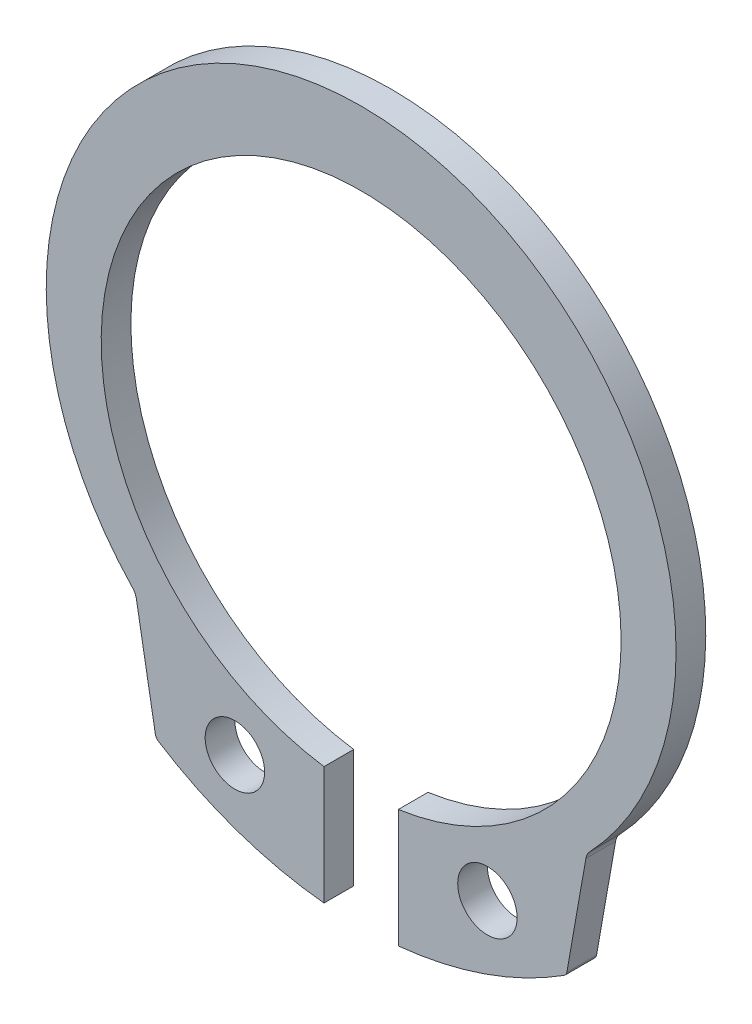
SolidWorks part; units mm, degrees
ref_plane "Front" through (0, 0, 0) normal (0, 0, 1) x (1, 0, 0)
ref_plane "Top" through (0, 0, 0) normal (0, 1, 0) x (1, 0, 0)
ref_plane "Right" through (0, 0, 0) normal (1, 0, 0) x (0, 0, -1)
sketch "Sketch1" plane through (0, 0, 0) normal (0, 0, 1) x (1, 0, 0)
  line L0 (0, 4.2365) -> (0, -4.9012) construction
  line L1 (-1.25, -9.2803) -> (-1.25, -13.2583)
  line L2 (1.25, -9.2803) -> (1.25, -13.2583)
  line L3 (10.7, -0.62) -> (-10.7, -0.62) construction
  line L4 (7.592, -7.3974) -> (6.908, -11.2769)
  line L7 (-7.592, -7.3974) -> (-6.908, -11.2769)
  line L8 (-7.592, -7.3974) -> (-7.592, -15.4681) construction
  arc A0 (1.25, -9.2803) -> (-1.25, -9.2803) centre (0, -0.62) ccw
  arc A1 (7.592, -7.3974) -> (-7.592, -7.3974) centre (0, 0) ccw
  arc A2 (-10.7, -0.62) -> (10.7, -0.62) centre (0, -0.62) ccw construction
  arc A3 (6.908, -11.2769) -> (1.25, -13.2583) centre (0, -0.62) cw
  arc A4 (-6.908, -11.2769) -> (-1.25, -13.2583) centre (0, -0.62) ccw
  circle A5 centre (4.25, -10.4398) radius 1
  circle A6 centre (-4.25, -10.4398) radius 1
  point P17 (-7.25, -9.3371)
  dimension "d" = 17.5
  dimension "D2" = 10
  dimension "d0" = 21.2
  dimension "d1" = 2
  dimension "R1" = 10.7
  dimension "R" = 12.7
  dimension "B1" = 2.5
  dimension "C" = 0.62
  dimension "L" = 14.5
  dimension "B2" = 8.5
extrude "Body" add sketch "Sketch1" against normal blind 1
fillet "Fillet1" radius 0.2 2 edges at (-6.908, -11.2769, -0.5) (6.908, -11.2769, -0.5)
fillet "Fillet2" radius 0.5 2 edges at (7.592, -7.3974, -0.5) (-7.592, -7.3974, -0.5)
